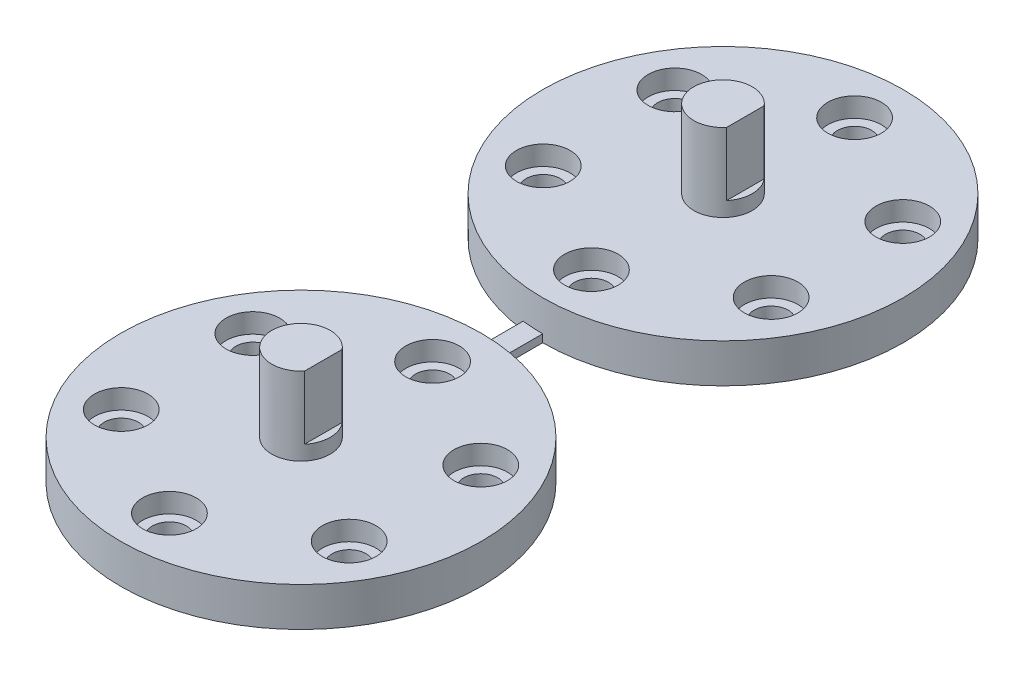
SolidWorks part; units mm, degrees
ref_plane "前视基准面" through (0, 0, 0) normal (0, 0, 1) x (1, 0, 0)
ref_plane "上视基准面" through (0, 0, 0) normal (0, 1, 0) x (1, 0, 0)
ref_plane "右视基准面" through (0, 0, 0) normal (1, 0, 0) x (0, 0, -1)
other "Configuration Table"
ref_plane "基准面1" through (0, 0, 0.9229) normal (0, 0, 1) x (1, 0, 0)
sketch "草图1" plane through (0, 0, 0.9229) normal (0, 0, 1) x (1, 0, 0)
  line L0 (19.1094, 4) -> (0.6094, 4)
  line L1 (0.6094, 4) -> (0.6094, 0)
  line L2 (0.6094, 0) -> (19.1094, 0)
  line L3 (19.1094, 0) -> (19.1094, 4)
  line L4 (0.6094, 4) -> (0.6094, 0) construction
revolve "旋转1" add sketch "草图1" angle 360 about L4
hole_wizard "M3 六角头机械螺钉的柱形沉头孔1" positions "草图7" profile "草图6" counterbore size "M3" standard "ANSI Metric" end condition through all
sketch "草图7" plane through (0, 4, 0) normal (0, 1, 0) x (1, 0, 0)
  point P0 (-11.082, -7.6729)
  point P1 (12.3007, -7.6729)
  point P2 (0.6094, 12.5771)
sketch "草图6" plane through (-11.082, 4, 7.6729) normal (1, 0, 0) x (0, 0, 1)
  line L0 (0, 0) -> (0, 4)
  line L1 (0, 4) -> (1.75, 4)
  line L3 (1.75, 4) -> (1.75, 2)
  line L4 (1.75, 2) -> (2.75, 2)
  line L5 (2.75, 2) -> (2.75, 0)
  line L7 (2.75, 0) -> (0, 0)
  line L11 (0, -6.35) -> (0, 107.95) construction
  dimension "通孔孔直径" = 3.5
  dimension "通孔孔深度" = 4
  dimension "柱形沉头孔直径" = 5.5
  dimension "柱形沉头孔深度" = 2
sketch "草图9" plane through (0, 0, 0) normal (0, -1, 0) x (1, 0, 0)
  circle A1 centre (0.6094, 0.9229) radius 4.0788
extrude "凸台-拉伸2" add sketch "草图9" against normal blind 4
sketch "草图10" plane through (0, 4, 0) normal (0, 1, 0) x (1, 0, 0)
  circle A0 centre (0.6094, -0.9229) radius 3
  point P0 (0.6094, -0.9229)
  dimension "D1" = 6
extrude "凸台-拉伸3" add sketch "草图10" along normal blind 8
sketch "草图11" plane through (0, 12, 0) normal (0, 1, 0) x (1, 0, 0)
  line L0 (2.9059, 1.0074) -> (2.9059, -2.8532)
  circle A0 centre (0.6094, -0.9229) radius 3 construction
  circle A1 centre (0.6094, -0.9229) radius 3 construction
  arc A2 (2.9059, -2.8532) -> (2.9059, 1.0074) centre (0.6094, -0.9229) ccw
extrude "切除-拉伸2" cut sketch "草图11" against normal blind 6.5
pattern_circular "阵列(圆周)1" count 3 every 60 about axis through (0.6094, 0, 0.9229) along (0, 1, 0) of "M3 六角头机械螺钉的柱形沉头孔1"
move or copy body "实体-移动/复制3"
sketch "草图13" plane through (0, 0, 0) normal (0, -1, 0) x (1, 0, 0)
  line L27 (-1.5166, 25.8415) -> (0.6094, 25.8415)
  line L28 (-1.5166, 25.8415) -> (-1.5166, 18.309)
  line L29 (-1.5166, 18.309) -> (0.6094, 18.309)
  line L30 (0.6094, 25.8415) -> (0.6094, 18.309)
  circle A0 centre (0.6094, 44.2189) radius 18.5 construction
extrude "凸台-拉伸4" add sketch "草图13" against normal blind 0.8 contours L30 L29 L28 L27
